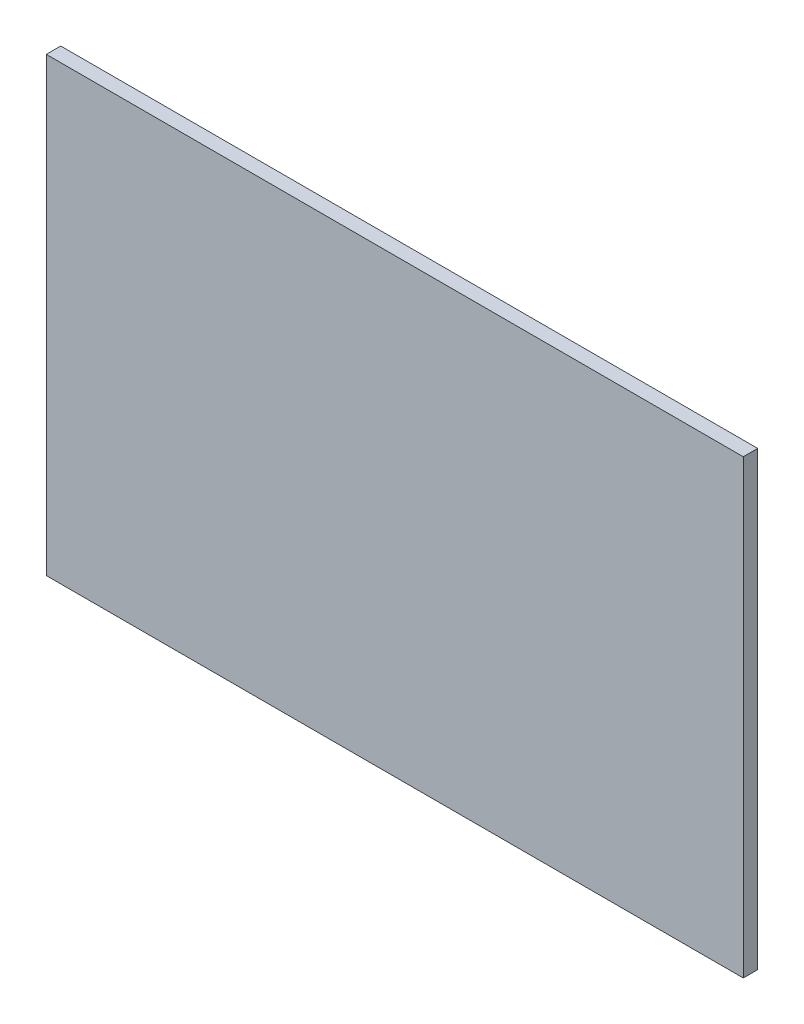
SolidWorks part; units mm, degrees
ref_plane "Front Plane" through (0, 0, 0) normal (0, 0, 1) x (1, 0, 0)
ref_plane "Top Plane" through (0, 0, 0) normal (0, 1, 0) x (1, 0, 0)
ref_plane "Right Plane" through (0, 0, 0) normal (1, 0, 0) x (0, 0, -1)
sketch "Sketch1" plane through (0, 0, 0) normal (0, 0, 1) x (1, 0, 0)
  line L1 (0, 0) -> (3860, 0)
  line L2 (0, 0) -> (0, 2500)
  line L3 (0, 2500) -> (3860, 2500)
  line L4 (3860, 0) -> (3860, 2500)
  dimension "D1" = 3860
  dimension "D2" = 2500
extrude "Boss-Extrude1" add sketch "Sketch1" along normal blind 80
